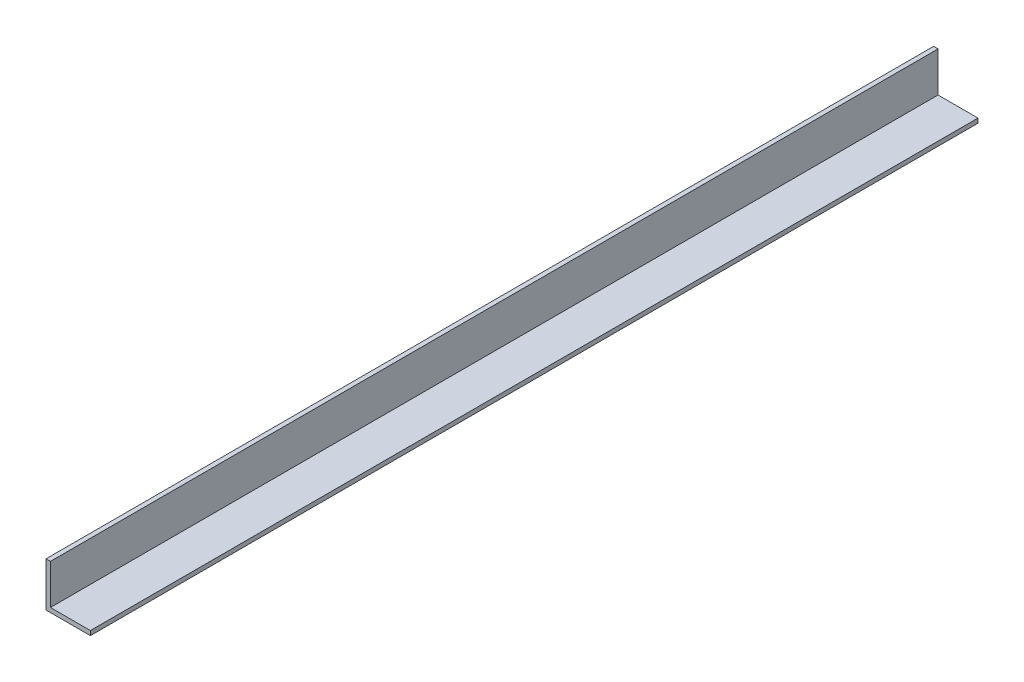
SolidWorks part; units mm, degrees
ref_plane "Front Plane" through (0, 0, 0) normal (0, 0, 1) x (1, 0, 0)
ref_plane "Top Plane" through (0, 0, 0) normal (0, 1, 0) x (1, 0, 0)
ref_plane "Right Plane" through (0, 0, 0) normal (1, 0, 0) x (0, 0, -1)
sketch "Sketch1" plane through (0, 0, 0) normal (0, 0, 1) x (1, 0, 0)
  line L0 (0, 0) -> (15, 0)
  line L1 (15, 0) -> (15, 1.5)
  line L2 (15, 1.5) -> (1.5, 1.5)
  line L3 (1.5, 1.5) -> (1.5, 15)
  line L4 (1.5, 15) -> (0, 15)
  line L5 (0, 15) -> (0, 0)
extrude "Boss-Extrude1" add sketch "Sketch1" along normal blind 300
